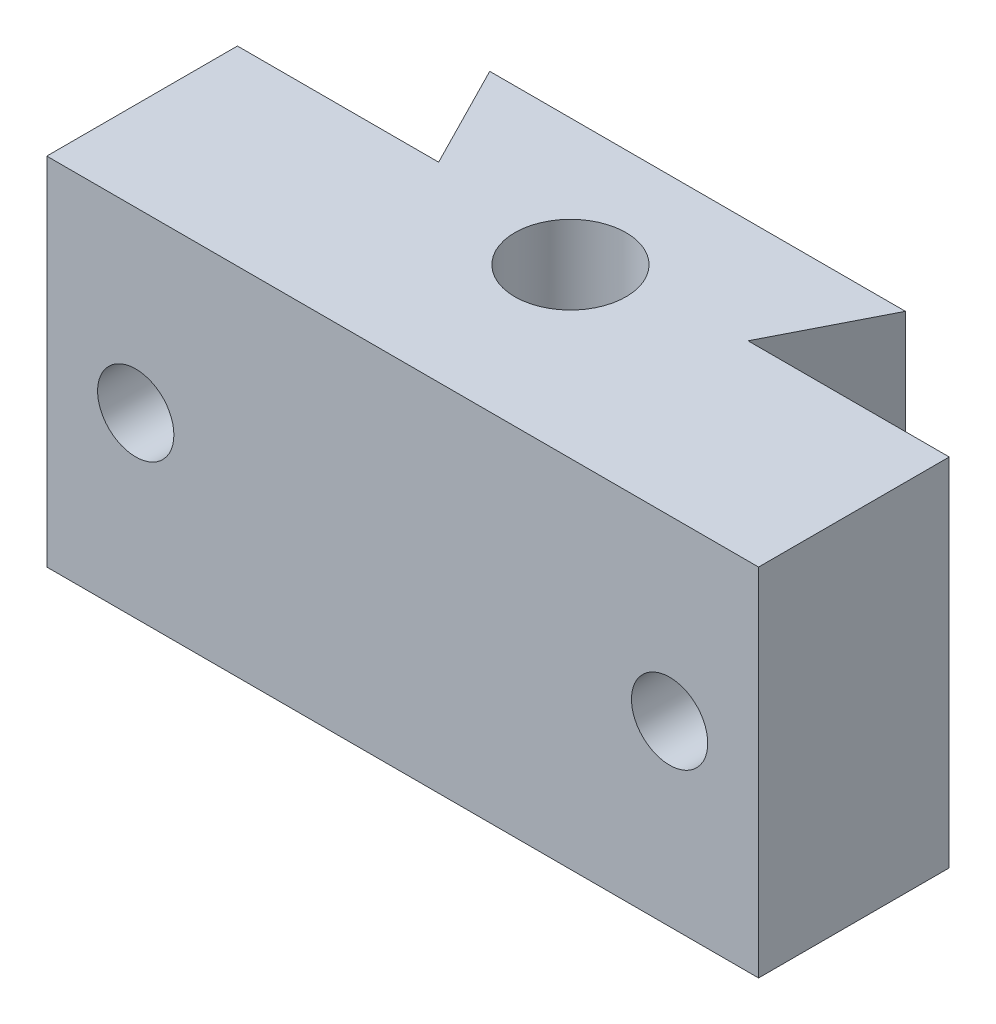
SolidWorks part; units mm, degrees
material "ABS"
ref_plane "Front" through (0, 0, 0) normal (0, 0, 1) x (1, 0, 0)
ref_plane "Top" through (0, 0, 0) normal (0, 1, 0) x (1, 0, 0)
ref_plane "Right" through (0, 0, 0) normal (1, 0, 0) x (0, 0, -1)
sketch "Sketch1" plane through (0, 0, 0) normal (0, 1, 0) x (1, 0, 0)
  line L0 (-12.1719, 7.5) -> (-16.35, 15.7)
  line L1 (-28, -7.5) -> (28, -7.5)
  line L2 (-28, -7.5) -> (-28, 7.5)
  line L3 (-28, 7.5) -> (28, 7.5)
  line L4 (28, -7.5) -> (28, 7.5)
  line L5 (-28, -7.5) -> (28, 7.5) construction
  line L6 (-28, 7.5) -> (28, -7.5) construction
  line L7 (-16.35, 15.7) -> (16.35, 15.7)
  line L8 (16.35, 15.7) -> (12.1719, 7.5)
  point P0 (0, 0)
  point P8 (0, 15.7)
  dimension "D1" = 56
  dimension "D2" = 15
  dimension "D3" = 32.7
  dimension "D4" = 8.2
  dimension "D5" = 117
extrude "Boss-Extrude1" add sketch "Sketch1" along normal mid plane 28 contours L8 L7 L0 L3 | L1 L4 L3 L2
sketch "Sketch2" plane through (0, 14, 0) normal (0, 1, 0) x (1, 0, 0)
  line L0 (-16.35, 15.7) -> (16.35, 15.7) construction
  circle A0 centre (0, 5.7) radius 4.375
  dimension "D1" = 8.75
  dimension "D2" = 10
extrude "Cut-Extrude1" cut sketch "Sketch2" against normal blind 28 contours A0
sketch "Sketch3" plane through (0, 0, 0) normal (0, -1, 0) x (1, 0, 0)
  line L0 (7.5056, -5.7) -> (7.5056, -15.7)
  line L1 (7.5056, -5.7) -> (3.7528, 0.8)
  line L2 (3.7528, 0.8) -> (-3.7528, 0.8)
  line L3 (-3.7528, 0.8) -> (-7.5056, -5.7)
  line L7 (-16.35, -15.7) -> (16.35, -15.7) construction
  line L8 (-7.5056, -5.7) -> (-7.5056, -15.7)
  line L9 (7.5056, -15.7) -> (-7.5056, -15.7)
  line L11 (-5.8457, -8.575) -> (-4.6188, -10.7) [skipped]
  line L12 (0, -12.2) -> (2.4537, -12.2) [skipped]
  line L13 (5.8457, -8.575) -> (7.0725, -6.45) [skipped]
  arc A0 (5.6292, -2.45) -> (-5.6292, -2.45) centre (0, -5.7) ccw construction
  dimension "D1" = 6.5
sketch "Sketch4" plane through (0, 0, 7.5) normal (0, 0, 1) x (1, 0, 0)
  line L0 (-28, 14) -> (-28, -14) construction
  line L1 (28, 14) -> (28, -14) construction
  circle A0 centre (-21, 0) radius 3
  circle A1 centre (21, 0) radius 3
  point P9 (-28, 0)
  point P11 (28, 0)
  dimension "D1" = 6
  dimension "D2" = 7
  dimension "D3" = 7
extrude "Cut-Extrude3" cut sketch "Sketch4" against normal up to surface (15 mm away) up to face at (-20.0859, 0, -7.5)
extrude "Cut-Extrude4" cut sketch "Sketch3" against normal mid plane 6.75
